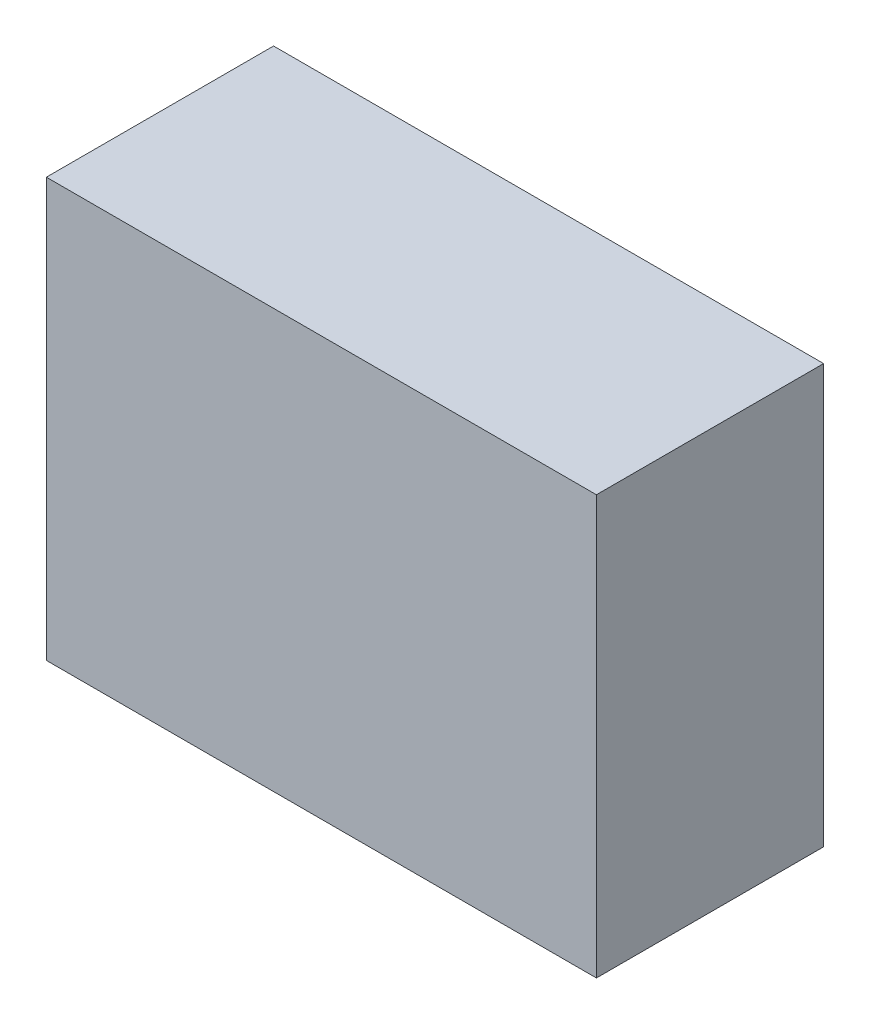
SolidWorks part; units mm, degrees
ref_plane "Front Plane" through (0, 0, 0) normal (0, 0, 1) x (1, 0, 0)
ref_plane "Top Plane" through (0, 0, 0) normal (0, 1, 0) x (1, 0, 0)
ref_plane "Right Plane" through (0, 0, 0) normal (1, 0, 0) x (0, 0, -1)
sketch "Sketch1" plane through (0, 0, 0) normal (0, 0, 1) x (1, 0, 0)
  line L1 (0, 0) -> (4.6, 0)
  line L2 (0, 0) -> (0, 3.5)
  line L3 (0, 3.5) -> (4.6, 3.5)
  line L4 (4.6, 0) -> (4.6, 3.5)
  dimension "D1" = 4.6
  dimension "D2" = 3.5
extrude "Boss-Extrude1" add sketch "Sketch1" along normal blind 1.9
